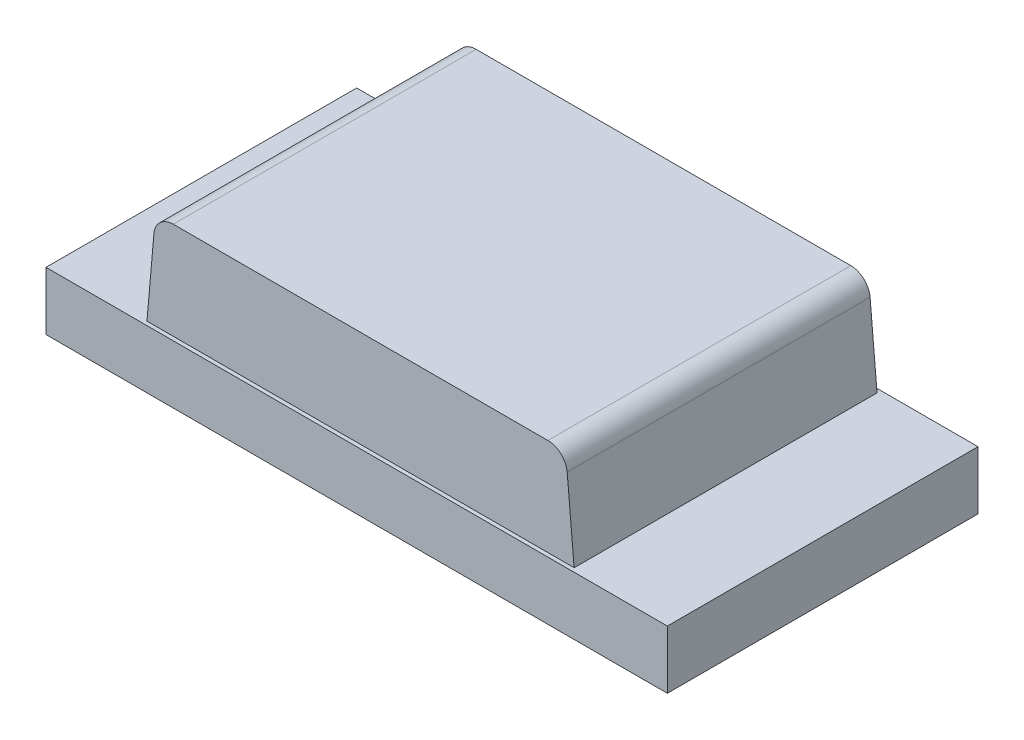
SolidWorks part; units mm, degrees
material "Alloy Steel"
ref_plane "Front Plane" through (0, 0, 0) normal (0, 0, 1) x (1, 0, 0)
ref_plane "Top Plane" through (0, 0, 0) normal (0, 1, 0) x (1, 0, 0)
ref_plane "Right Plane" through (0, 0, 0) normal (1, 0, 0) x (0, 0, -1)
sketch "Sketch1" plane through (0, 0, 0) normal (0, 1, 0) x (1, 0, 0)
  line L1 (0.8, -0.4) -> (-0.8, -0.4)
  line L2 (0.8, -0.4) -> (0.8, 0.4)
  line L3 (0.8, 0.4) -> (-0.8, 0.4)
  line L4 (-0.8, -0.4) -> (-0.8, 0.4)
  line L5 (0.8, -0.4) -> (-0.8, 0.4) construction
  line L6 (0.8, 0.4) -> (-0.8, -0.4) construction
  point P0 (0, 0)
  dimension "D1" = 0.8
  dimension "D2" = 1.6
extrude "Base" add sketch "Sketch1" along normal blind 0.15
sketch "Sketch2" plane through (0, 0, 0) normal (0, 0, 1) x (1, 0, 0)
  line L0 (-0.55, 0.15) -> (-0.5281, 0.4)
  line L1 (-0.8, 0.15) -> (0.8, 0.15) construction
  line L2 (-0.5281, 0.4) -> (0.5281, 0.4)
  line L3 (0.5281, 0.4) -> (0.55, 0.15)
  line L4 (0.55, 0.15) -> (-0.55, 0.15)
  line L5 (0.44, 0) -> (-0.44, 0) construction
  line L6 (0, -0.3025) -> (0, 0.3025) construction
  point P8 (0, 0.4)
  dimension "D1" = 1.1
  dimension "D2" = 0.4
  dimension "D3" = 10
extrude "Lens" add sketch "Sketch2" along normal offset from surface 0.01 and the other way offset from surface (0.39 mm away) 0.01 up to face at (0, 0.075, 0.4) other way up to face at (0, 0.075, -0.4)
fillet "Lens Rounds" radius 0.05 2 edges at (0.5281, 0.4, 0) (-0.5281, 0.4, 0)
